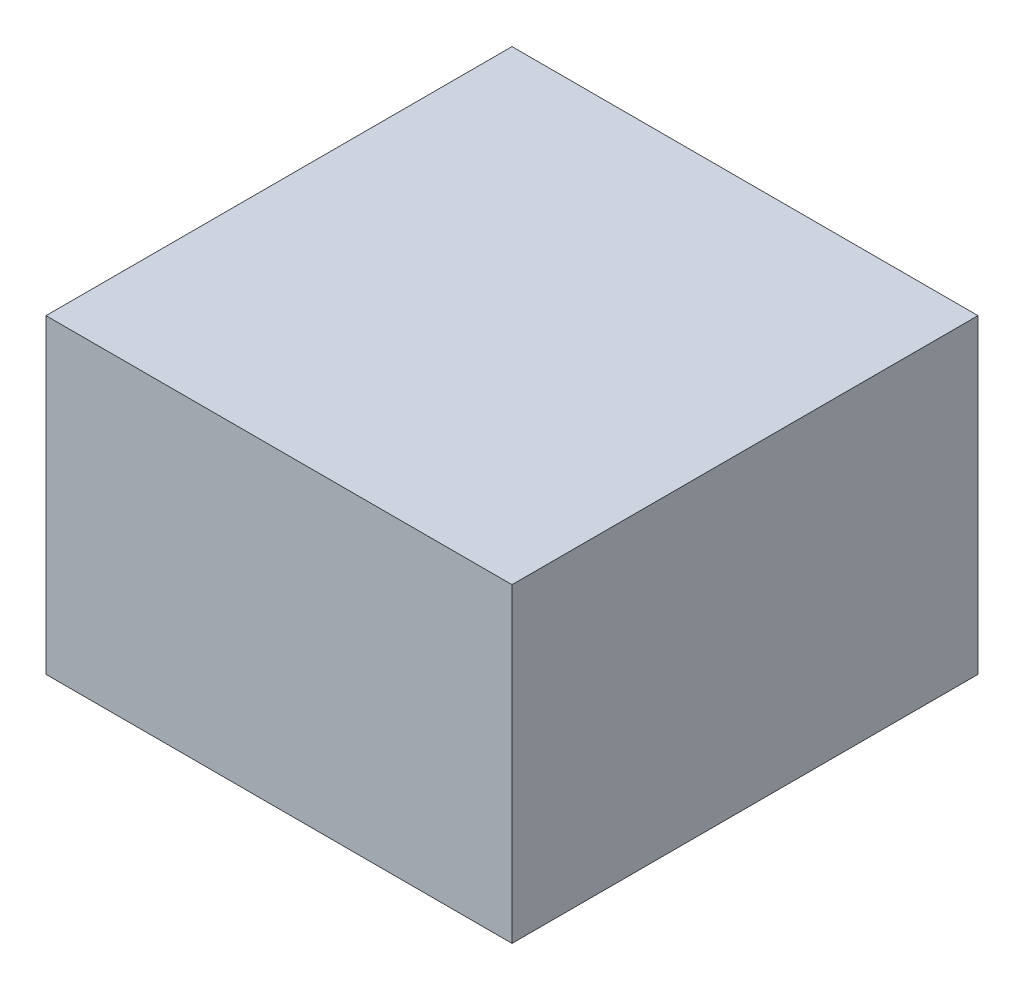
SolidWorks part; units mm, degrees
ref_plane "Front Plane" through (0, 0, 0) normal (0, 0, 1) x (1, 0, 0)
ref_plane "Top Plane" through (0, 0, 0) normal (0, 1, 0) x (1, 0, 0)
ref_plane "Right Plane" through (0, 0, 0) normal (1, 0, 0) x (0, 0, -1)
sketch "Sketch1" plane through (0, 0, 0) normal (0, 1, 0) x (1, 0, 0)
  line L1 (0, 0) -> (150, 0)
  line L2 (0, 0) -> (0, -150)
  line L3 (0, -150) -> (150, -150)
  line L4 (150, 0) -> (150, -150)
  dimension "D1" = 150
  dimension "D2" = 150
extrude "Boss-Extrude1" add sketch "Sketch1" along normal blind 100
